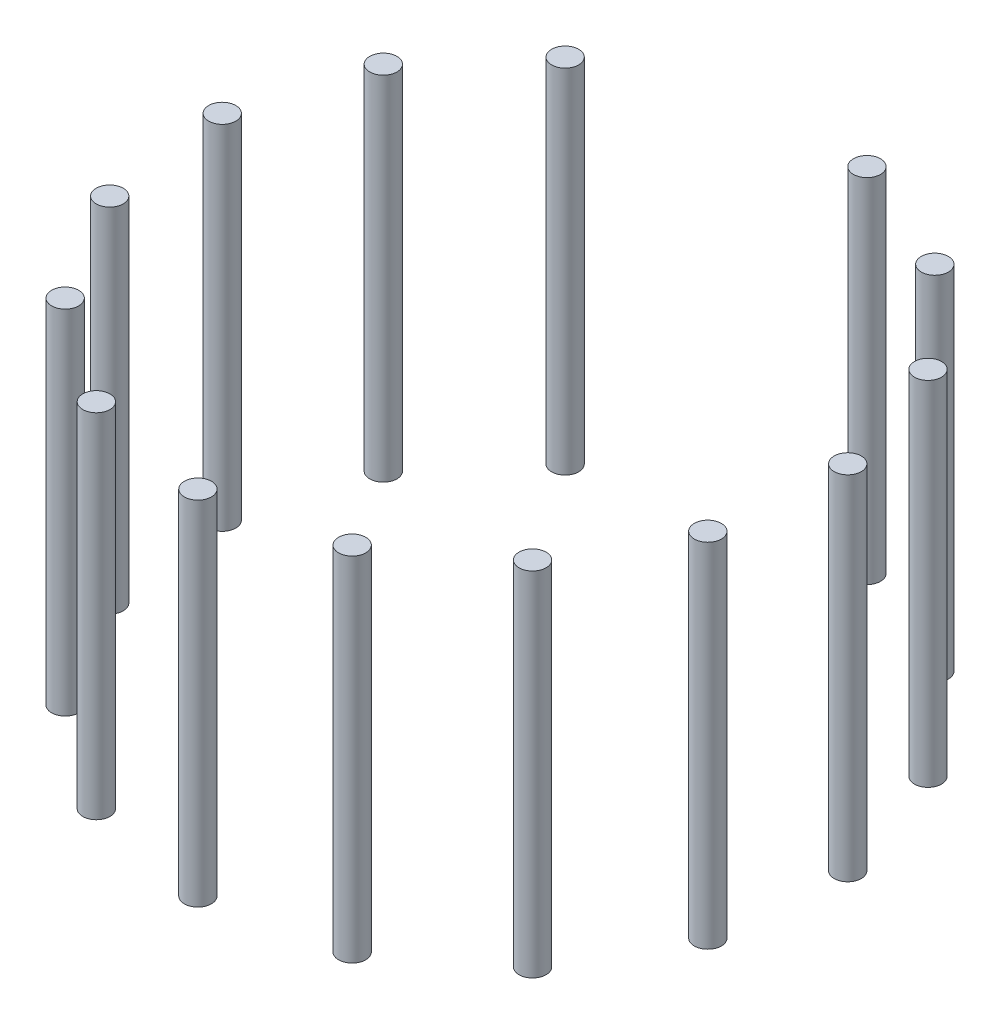
SolidWorks part; units mm, degrees
ref_plane "Front Plane" through (0, 0, 0) normal (0, 0, 1) x (1, 0, 0)
ref_plane "Top Plane" through (0, 0, 0) normal (0, 1, 0) x (1, 0, 0)
ref_plane "Right Plane" through (0, 0, 0) normal (1, 0, 0) x (0, 0, -1)
sketch "Sketch1" plane through (0, 0, 0) normal (0, 1, 0) x (1, 0, 0)
  line L0 (13.4437, 1.3155) -> (12.1086, 7.1651) construction
  line L1 (12.1086, 7.1651) -> (11.6635, 9.115) construction
  circle A0 centre (14.9897, 9.1647) radius 0.35
  circle A1 centre (18.0486, 7.8573) radius 0.35
  circle A2 centre (20.3113, 5.4187) radius 0.35
  circle A3 centre (21.3865, 2.2707) radius 0.35
  circle A4 centre (21.0883, -1.0425) radius 0.35
  circle A5 centre (19.4683, -3.948) radius 0.35
  circle A6 centre (16.8066, -5.9433) radius 0.35
  circle A7 centre (13.5634, -6.6836) radius 0.35
  circle A8 centre (10.2995, -6.0407) radius 0.35
  circle A9 centre (7.5793, -4.1258) radius 0.35
  circle A10 centre (5.8731, -1.2701) radius 0.35
  circle A11 centre (5.4759, 2.0327) radius 0.35
  circle A12 centre (6.4564, 5.2115) radius 0.35
  circle A13 centre (8.6451, 7.7166) radius 0.35
extrude "Boss-Extrude1" add sketch "Sketch1" along normal blind 9.1
